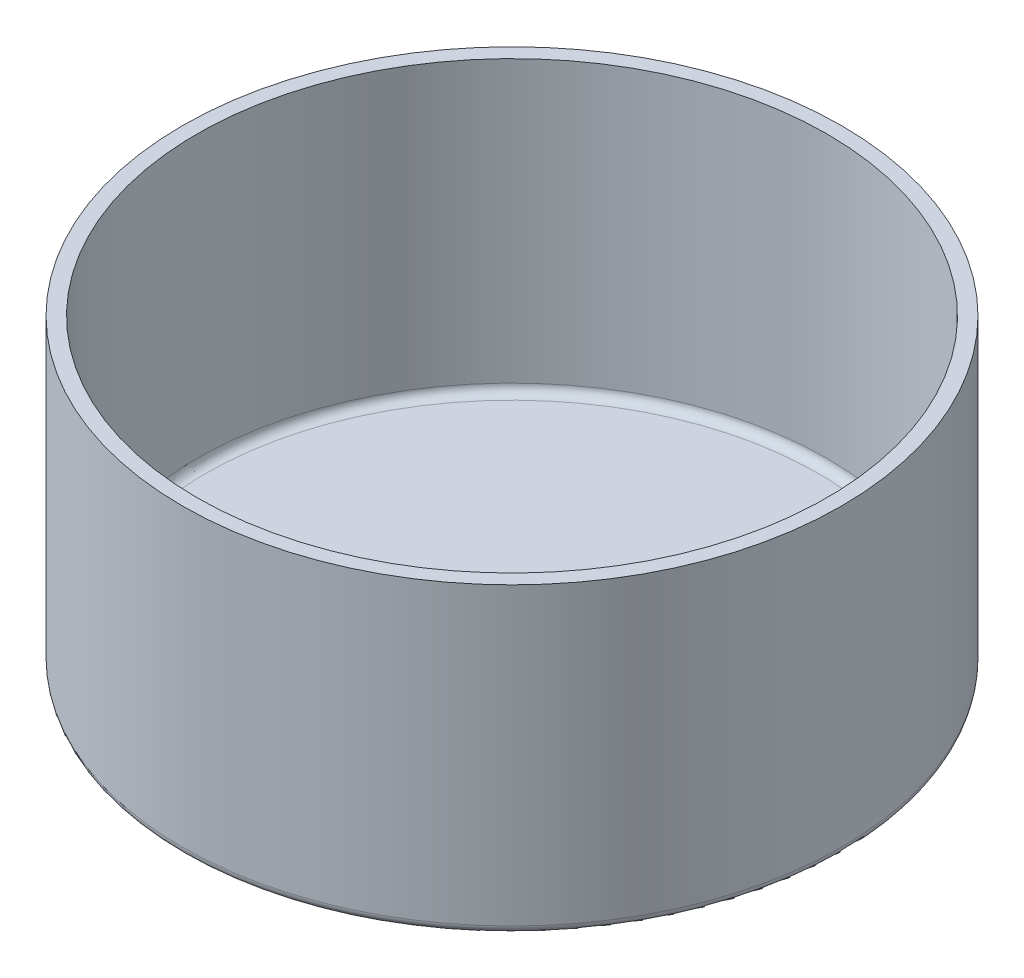
SolidWorks part; units mm, degrees
ref_plane "Alzado" through (0, 0, 0) normal (0, 0, 1) x (1, 0, 0)
ref_plane "Planta" through (0, 0, 0) normal (0, 1, 0) x (1, 0, 0)
ref_plane "Vista lateral" through (0, 0, 0) normal (1, 0, 0) x (0, 0, -1)
sketch "Croquis1" plane through (0, 0, 0) normal (0, 1, 0) x (1, 0, 0)
  circle A0 centre (0, 0) radius 11.375
  dimension "D1" = 22.75
extrude "Saliente-Extruir1" add sketch "Croquis1" along normal blind 0.5
sketch "Croquis2" plane through (0, 0.5, 0) normal (0, 1, 0) x (1, 0, 0)
  circle A0 centre (0, 0) radius 11.375
  circle A1 centre (0, 0) radius 10.875
  dimension "D1" = 22.75
  dimension "D2" = 21.75
extrude "Saliente-Extruir2" add sketch "Croquis2" along normal blind 10
fillet "Redondeo1" radius 0.3 1 edges at (0, 0.5, 10.875)
fillet "Redondeo2" radius 0.3 1 edges at (0, 0, 11.375)
